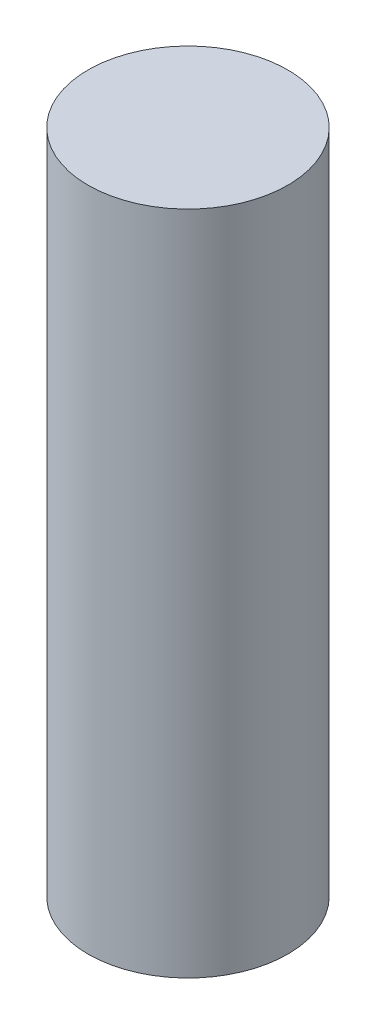
SolidWorks part; units mm, degrees
ref_plane "前视基准面" through (0, 0, 0) normal (0, 0, 1) x (1, 0, 0)
ref_plane "上视基准面" through (0, 0, 0) normal (0, 1, 0) x (1, 0, 0)
ref_plane "右视基准面" through (0, 0, 0) normal (1, 0, 0) x (0, 0, -1)
other "Configuration Table"
sketch "草图1" plane through (0, 0, 0) normal (0, 1, 0) x (1, 0, 0)
  circle A0 centre (0, 0) radius 150
  dimension "D1" = 300
extrude "凸台-拉伸1" add sketch "草图1" along normal blind 1000
